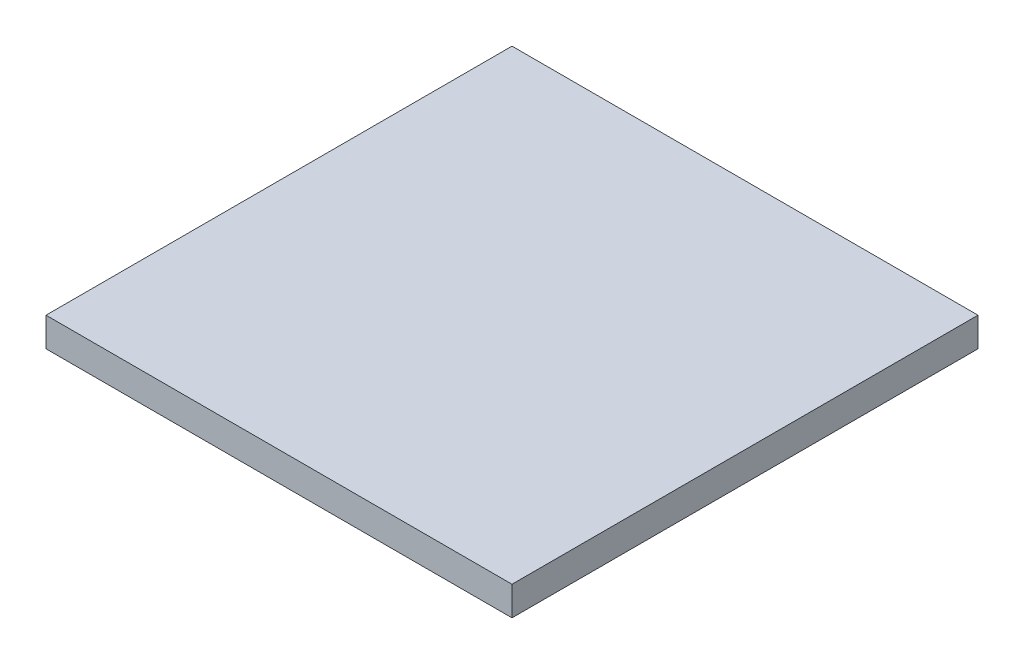
SolidWorks part; units mm, degrees
ref_plane "Front Plane" through (0, 0, 0) normal (0, 0, 1) x (1, 0, 0)
ref_plane "Top Plane" through (0, 0, 0) normal (0, 1, 0) x (1, 0, 0)
ref_plane "Right Plane" through (0, 0, 0) normal (1, 0, 0) x (0, 0, -1)
sketch "Sketch1" plane through (0, 0, 0) normal (0, 1, 0) x (1, 0, 0)
  line L1 (0, 0) -> (-101.6, 0)
  line L2 (0, 0) -> (0, 101.6)
  line L3 (0, 101.6) -> (-101.6, 101.6)
  line L4 (-101.6, 0) -> (-101.6, 101.6)
  dimension "D1" = 101.6
  dimension "D2" = 101.6
extrude "Boss-Extrude1" add sketch "Sketch1" along normal blind 6.35
